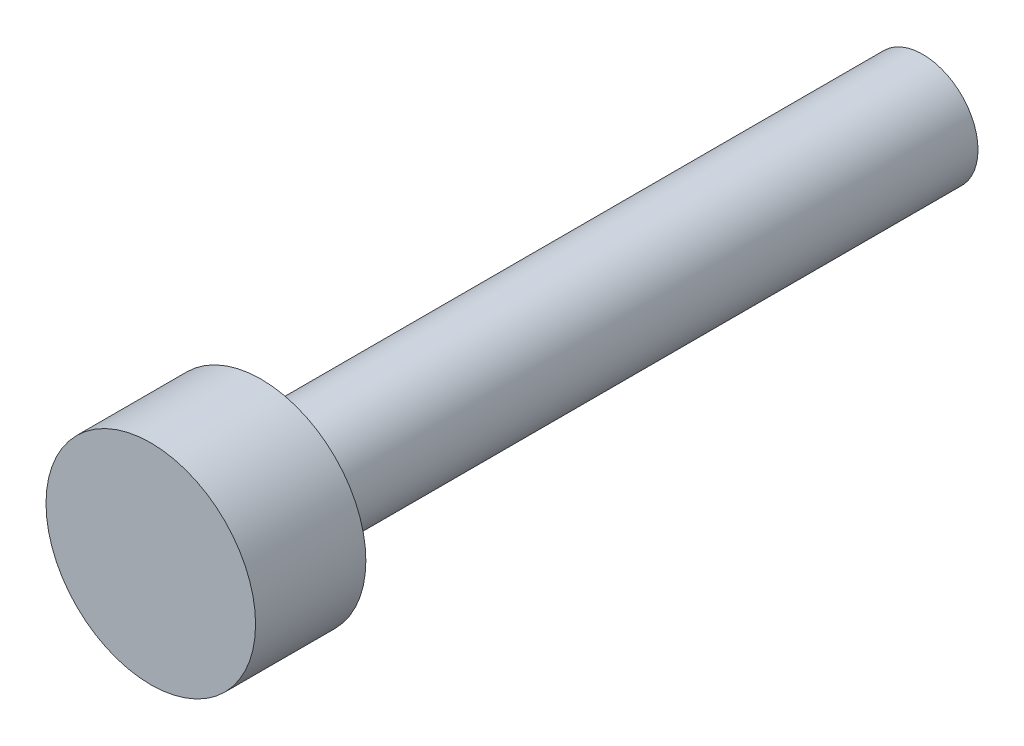
SolidWorks part; units mm, degrees
ref_plane "Front Plane" through (0, 0, 0) normal (0, 0, 1) x (1, 0, 0)
ref_plane "Top Plane" through (0, 0, 0) normal (0, 1, 0) x (1, 0, 0)
ref_plane "Right Plane" through (0, 0, 0) normal (1, 0, 0) x (0, 0, -1)
sketch "Sketch1" plane through (0, 0, 0) normal (0, 0, 1) x (1, 0, 0)
  circle A0 centre (0, 0) radius 1
extrude "M2x0p4_Thread_Envelope_L12" add sketch "Sketch1" along normal blind 12 from offset 12
sketch "Sketch2" plane through (0, 0, 0) normal (0, 0, 1) x (1, 0, 0)
  circle A0 centre (0, 0) radius 1.9
extrude "Head_D3p8_H2" add sketch "Sketch2" along normal blind 2
